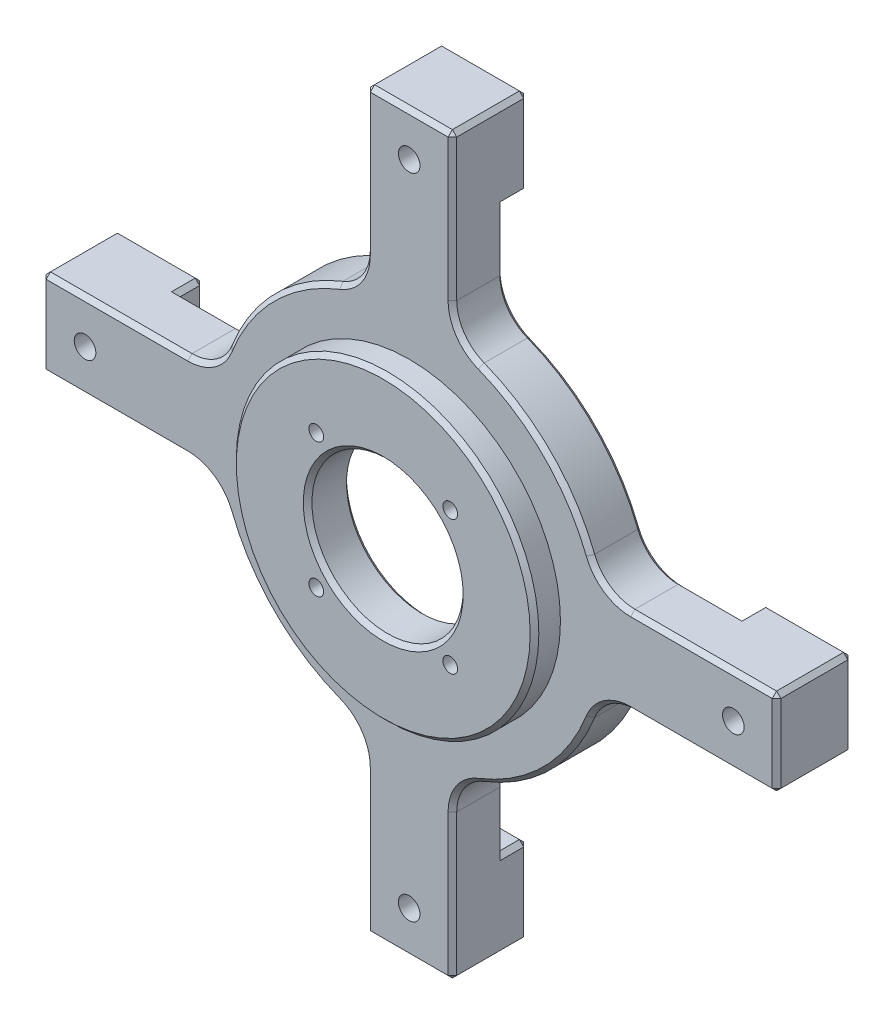
SolidWorks part; units mm, degrees
ref_plane "Front" through (0, 0, 0) normal (0, 0, 1) x (1, 0, 0)
ref_plane "Top" through (0, 0, 0) normal (0, 1, 0) x (1, 0, 0)
ref_plane "Right" through (0, 0, 0) normal (1, 0, 0) x (0, 0, -1)
sketch "Sketch1" plane through (0, 0, 0) normal (0, 0, 1) x (1, 0, 0)
  line L0 (85, 0) -> (0, 0) construction
  line L1 (43.8748, -10) -> (85, -10)
  line L2 (0, 0) -> (-85, 0) construction
  line L3 (43.8748, 10) -> (85, 10)
  line L4 (85, -10) -> (85, 10)
  line L5 (0, -85) -> (0, 0) construction
  line L6 (10, 43.8748) -> (10, 85)
  line L7 (10, 85) -> (-10, 85)
  line L8 (-10, 43.8748) -> (-10, 85)
  line L9 (-43.8748, 10) -> (-85, 10)
  line L10 (0, 0) -> (0, 85) construction
  line L11 (-43.8748, -10) -> (-85, -10)
  line L12 (-85, 10) -> (-85, -10)
  line L14 (10, -43.8748) -> (10, -85)
  line L15 (10, -85) -> (-10, -85)
  line L16 (-10, -43.8748) -> (-10, -85)
  arc A0 (43.8748, 10) -> (10, 43.8748) centre (0, 0) ccw
  circle A1 centre (0, 0) radius 35
  arc A2 (-10, 43.8748) -> (-43.8748, 10) centre (0, 0) ccw
  arc A3 (-43.8748, -10) -> (-10, -43.8748) centre (0, 0) ccw
  arc A4 (10, -43.8748) -> (43.8748, -10) centre (0, 0) ccw
  dimension "D1" = 90
  dimension "D2" = 70
  dimension "D3" = 20
  dimension "D4" = 85
extrude "Boss-Extrude1" add sketch "Sketch1" along normal blind 12
sketch "Sketch2" plane through (0, 0, 12) normal (0, 0, 1) x (1, 0, 0)
  circle A0 centre (0, 0) radius 35
  circle A1 centre (0, 0) radius 17.5
  circle A2 centre (0, 0) radius 35 construction
  dimension "D1" = 35
extrude "Boss-Extrude2" add sketch "Sketch2" against normal blind 4
sketch "Sketch3" plane through (0, 0, 0) normal (0, 0, 1) x (1, 0, 0)
  line L3 (10, 85) -> (-10, 85) construction
  line L7 (10, 85) -> (-10, 85)
  line L8 (10, 85) -> (10, 65)
  line L9 (10, 43.8748) -> (10, 85) construction
  line L10 (10, 65) -> (-10, 65)
  line L11 (-10, 85) -> (-10, 43.8748) construction
  line L12 (-10, 65) -> (-10, 85)
  dimension "D1" = 20
extrude "Boss-Extrude3" add sketch "Sketch3" against normal blind 5.5
pattern_circular "CirPattern1" count 4 every 90 about axis through (0, 0, 0) along (0, 0, 1) of "Boss-Extrude3"
sketch "Sketch4" plane through (0, 0, -5.5) normal (0, 0, -1) x (-1, 0, 0)
  line L0 (0, 75) -> (0, 0) construction
  line L1 (0, 0) -> (0, -75) construction
  line L2 (75, 0) -> (0, 0) construction
  line L3 (-75, 0) -> (0, 0) construction
  line L4 (0, 85) -> (0, 75) construction
  line L5 (-10, 85) -> (10, 85) construction
  line L6 (0, 75) -> (0, 65) construction
  line L7 (10, 65) -> (-10, 65) construction
  line L8 (-65, 0) -> (-75, 0) construction
  line L9 (-65, 10) -> (-65, -10) construction
  line L10 (-75, 0) -> (-85, 0) construction
  line L11 (-85, -10) -> (-85, 10) construction
  circle A0 centre (0, 75) radius 2.5
  circle A1 centre (-75, 0) radius 2.5
  circle A2 centre (0, -75) radius 2.5
  circle A3 centre (75, 0) radius 2.5
  dimension "D1" = 5
extrude "Cut-Extrude1" cut sketch "Sketch4" against normal up to next
fillet "Fillet2" radius 10 8 edges at (-43.8748, 10, 6) (-10, 43.8748, 6) (-43.8748, -10, 6) (-10, -43.8748, 6) (10, -43.8748, 6) (43.8748, -10, 6) (43.8748, 10, 6) (10, 43.8748, 6)
sketch "Sketch5" plane through (0, 0, 12) normal (0, 0, 1) x (1, 0, 0)
  circle A0 centre (0, 0) radius 17.5
  circle A1 centre (0, 0) radius 35
  circle A2 centre (0, 0) radius 17.5 construction
  dimension "D1" = 70
extrude "Boss-Extrude4" add sketch "Sketch5" along normal blind 6
hole_wizard "CSK for M3 Countersunk Flat Head Screw1" positions "3DSketch2" profile "Sketch7" countersink size "M3" standard "ISO" end condition up to next
sketch3d "3DSketch2"
  line L5 (0, 0, 8) -> (-15.5, 15.5, 8) construction
  line L6 (0, 0, 8) -> (0, 0, 18) construction
  line L7 (0, 0, 8) -> (0, 0, 0) construction
  line L9 (0, 0, 8) -> (15.5, 15.5, 8) construction
  line L11 (0, 0, 8) -> (-15.5, -15.5, 8) construction
  line L13 (0, 0, 8) -> (15.5, -15.5, 8) construction
  point P0 (-15.5, 15.5, 8)
  point P2 (15.5, 15.5, 8)
  point P4 (15.5, -15.5, 8)
  point P6 (-15.5, -15.5, 8)
  dimension "D1" = 31
sketch "Sketch7" plane through (-15.5, 15.5, 8) normal (1, 0, 0) x (0, 1, 0)
  line L0 (0, 0) -> (0, 10)
  line L1 (0, 10) -> (1.7, 10)
  line L2 (1.7, 10) -> (1.7, 1.45)
  line L3 (1.7, 1.45) -> (3.15, 0)
  line L5 (3.15, 0) -> (0, 0)
  line L6 (-1.7, 1.45) -> (-3.15, 0) construction
  line L11 (0, -6.35) -> (0, 107.95) construction
  dimension "Thru Hole Dia." = 3.4
  dimension "Thru Hole Depth" = 10
  dimension "Near C'Sink Dia." = 6.3
  dimension "Near C'Sink Angle" = 90
chamfer "Chamfer1" distance 1 angle 45 76 edges at (10, 85, 3.25) (-10, 85, 3.25) (10, 75, -5.5) (0, 85, -5.5) (-10, 75, -5.5) (0, 65, -5.5) (85, -10, 3.25) (85, 10, 3.25) (75, -10, -5.5) (75, 10, -5.5) (65, 0, -5.5) (85, 0, -5.5) (10, -85, 3.25) (-10, -85, 3.25) (-10, -75, -5.5) (10, -75, -5.5) (0, -65, -5.5) (0, -85, -5.5) (-85, -10, 3.25) (-85, 10, 3.25) (-75, 10, -5.5) (-75, -10, -5.5) (-65, 0, -5.5) (-85, 0, -5.5) (10, -58.1174, 0) (58.1174, -10, 0) (11.7428, -45.594, 0) (45.594, -11.7428, 0) (31.8198, -31.8198, 0) (58.1174, 10, 0) (10, 58.1174, 0) (45.594, 11.7428, 0) (11.7428, 45.594, 0) (31.8198, 31.8198, 0) (-10, 68.1174, 12) (-68.1174, 10, 12) (-11.7428, 45.594, 12) (-45.594, 11.7428, 12) (-31.8198, 31.8198, 12) (68.1174, 10, 12) (45.594, 11.7428, 12) (31.8198, 31.8198, 12) (11.7428, 45.594, 12) (0, 85, 12) (10, 68.1174, 12) (-10, 65, -2.75) (10, 65, -2.75) (10, -68.1174, 12) (11.7428, -45.594, 12) (31.8198, -31.8198, 12) (45.594, -11.7428, 12) (68.1174, -10, 12) (85, 0, 12) (65, 10, -2.75) (65, -10, -2.75) (-68.1174, -10, 12) (-45.594, -11.7428, 12) (-31.8198, -31.8198, 12) (-11.7428, -45.594, 12) (-10, -68.1174, 12) (0, -85, 12) (10, -65, -2.75) (-10, -65, -2.75) (-10, -58.1174, 0) (-10, 58.1174, 0) (-11.7428, -45.594, 0) (-11.7428, 45.594, 0) (-31.8198, -31.8198, 0) (-31.8198, 31.8198, 0) (-45.594, -11.7428, 0) (-45.594, 11.7428, 0) (-58.1174, -10, 0) (-58.1174, 10, 0) (-85, 0, 12) (-65, -10, -2.75) (-65, 10, -2.75)
chamfer "Chamfer2" distance 1 angle 45 4 edges at (35, 0, 0) (17.5, 0, 8) (17.5, 0, 18) (35, 0, 18)
